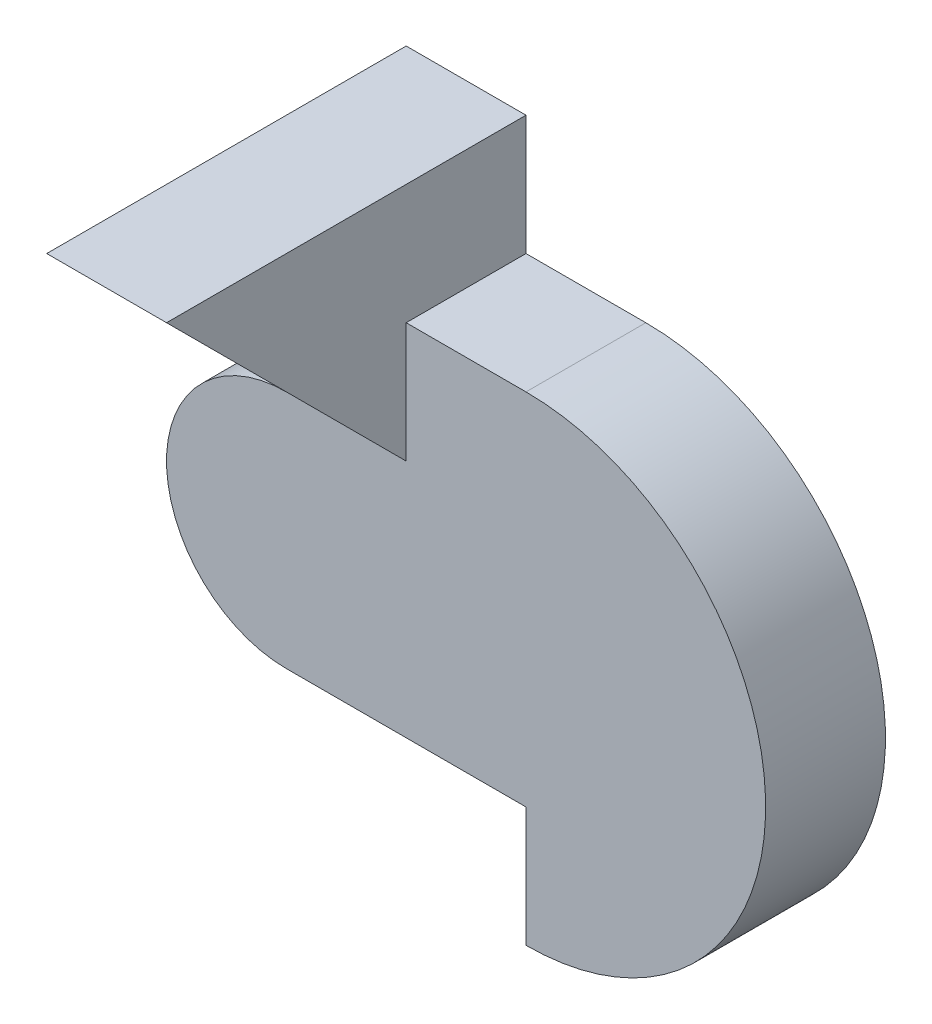
SolidWorks part; units mm, degrees
ref_plane "Płaszczyzna przednia" through (0, 0, 0) normal (0, 0, 1) x (1, 0, 0)
ref_plane "Płaszczyzna górna" through (0, 0, 0) normal (0, 1, 0) x (1, 0, 0)
ref_plane "Płaszczyzna prawa" through (0, 0, 0) normal (1, 0, 0) x (0, 0, -1)
sketch "Szkic1" plane through (0, 0, 0) normal (0, 0, 1) x (1, 0, 0)
  line L0 (71.4803, 0) -> (-88.6102, 0) construction
  line L1 (0, -10) -> (-20, -10)
  line L2 (-20, 10) -> (-10, 10)
  line L3 (-10, 10) -> (-10, 20)
  line L4 (-10, 20) -> (0, 20)
  line L5 (0, -10) -> (0, -20)
  arc A0 (-20, -10) -> (-30, 0) centre (-20, 0) cw
  arc A1 (-30, 0) -> (-20, 10) centre (-20, 0) cw
  arc A2 (0, -20) -> (0, 20) centre (0, 0) ccw
  point P14 (0, 0)
  point P15 (0, 0)
  point P16 (0, 0)
  point P17 (0, 0)
  point P18 (0, 0)
  point P19 (0, 0)
  point P20 (0, 0)
  dimension "D3" = 10
  dimension "D4" = 10
  dimension "D5" = 20
  dimension "D1" = 20
  dimension "D2" = 10
  dimension "D6" = 10
  dimension "D7" = 10
extrude "Dodanie-wyciągnięcie1" add sketch "Szkic1" along normal blind 10
sketch "Szkic2" plane through (0, 0, 0) normal (0, 0, 1) x (1, 0, 0)
  line L0 (-10, 10) -> (-20, 10)
  line L1 (-10, 10) -> (-20, 10) construction
  line L2 (-20, 10) -> (-20, 30)
  line L3 (-20, 30) -> (-10, 30)
  line L4 (-10, 30) -> (-10, 10)
  arc A0 (-20, 10) -> (-20, -10) centre (-20, 0) ccw construction
  dimension "D1" = 10
  dimension "D2" = 20
extrude "Dodanie-wyciągnięcie2" add sketch "Szkic2" along normal blind 30
sketch "Szkic3" plane through (-10, 0, 0) normal (1, 0, 0) x (0, 0, -1)
  line L0 (-10, 10) -> (-30, 30)
  line L1 (-30, 30) -> (-30, 10)
  line L2 (-30, 10) -> (-10, 10)
extrude "Wytnij-wyciągnięcie1" cut sketch "Szkic3" against normal blind 30
